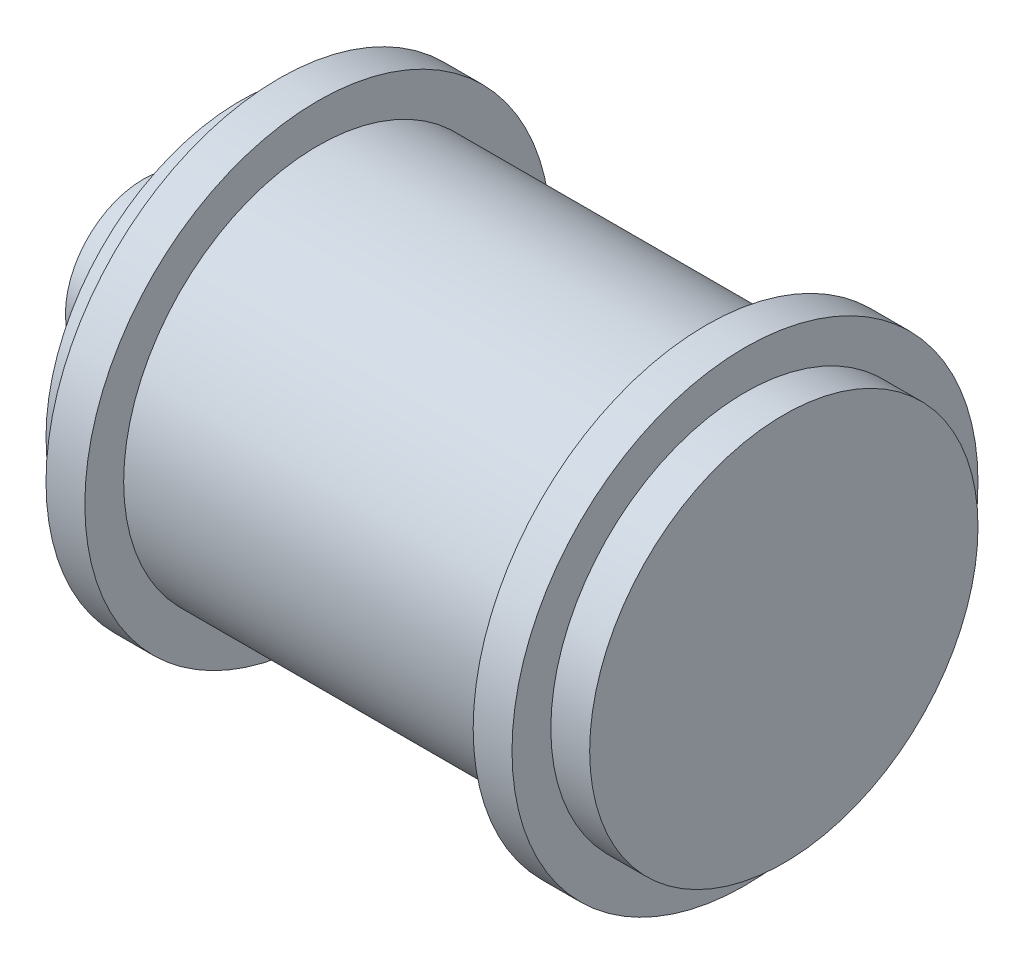
SolidWorks part; units mm, degrees
ref_plane "Front Plane" through (0, 0, 0) normal (0, 0, 1) x (1, 0, 0)
ref_plane "Top Plane" through (0, 0, 0) normal (0, 1, 0) x (1, 0, 0)
ref_plane "Right Plane" through (0, 0, 0) normal (1, 0, 0) x (0, 0, -1)
sketch "Sketch1" plane through (0, 0, 0) normal (1, 0, 0) x (0, 0, -1)
  circle A0 centre (0, 0) radius 50
  dimension "D1" = 100
extrude "Boss-Extrude1" add sketch "Sketch1" along normal blind 140
sketch "Sketch2" plane through (0, 0, 0) normal (0, 1, 0) x (1, 0, 0)
  line L0 (0, 0) -> (140, 0) construction
  line L1 (0, 50) -> (0, -50) construction
  line L2 (140, -50) -> (140, 50) construction
  line L3 (20, 60) -> (20, 0)
  line L4 (70, 50) -> (70, -150.463) construction
  line L5 (140, 50) -> (0, 50) construction
  line L6 (20, 60) -> (10, 60)
  line L7 (10, 60) -> (10, 0)
  line L8 (10, 0) -> (20, 0)
  line L9 (130, 0) -> (120, 0)
  line L10 (120, 60) -> (130, 60)
  line L11 (120, 60) -> (120, 0)
  line L12 (130, 60) -> (130, 0)
  dimension "D1" = 10
  dimension "D2" = 50
  dimension "D3" = 60
revolve "Revolve1" add sketch "Sketch2" angle 360 about L0
sketch "Sketch3" plane through (0, 0, 0) normal (-1, 0, 0) x (0, 0, 1)
  circle A1 centre (0, 0) radius 50
  circle A2 centre (0, 0) radius 50
  dimension "D1" = 0
extrude "Boss-Extrude2" add sketch "Sketch3" along normal blind 100
sketch "Sketch4" plane through (-100, 0, 0) normal (-1, 0, 0) x (0, 0, 1)
  circle A0 centre (0, 0) radius 169.2682
  dimension "D1" = 338.5363
extrude "Boss-Extrude3" add sketch "Sketch4" along normal blind 10
fillet "Fillet2" radius 50 1 edges at (-100, 0, 50)
sketch "Sketch5" plane through (0, 0, 0) normal (0, 0, 1) x (1, 0, 0)
  line L0 (10, 60) -> (10, -60) construction
  line L1 (-246.2995, -184.8189) -> (-25, -184.8189)
  line L2 (-246.2995, -184.8189) -> (-246.2995, 173.7056)
  line L3 (-246.2995, 173.7056) -> (-25, 173.7056)
  line L4 (-25, -184.8189) -> (-25, 173.7056)
  line L5 (-246.2995, -184.8189) -> (-25, 173.7056) construction
  line L6 (-246.2995, 173.7056) -> (-25, -184.8189) construction
  point P0 (-135.6497, -5.5566)
  dimension "D1" = 35
extrude "Cut-Extrude1" cut sketch "Sketch5" against normal through all both and the other way through all
sketch "Sketch6" plane through (0, 0, 0) normal (0, 1, 0) x (1, 0, 0)
  line L0 (-42.7701, 0) -> (167.9609, 0) construction
  line L1 (-37.1236, 20) -> (0, 20)
  line L2 (0, 20) -> (0, 63.4195)
  line L3 (0, 63.4195) -> (-45.1306, 53.302)
  line L4 (-45.1306, 53.302) -> (-37.1236, 20)
  line L5 (10, 60) -> (10, -60) construction
  dimension "D1" = 10
  dimension "D2" = 20
revolve "Cut-Revolve1" cut sketch "Sketch6" angle 360 about L0
